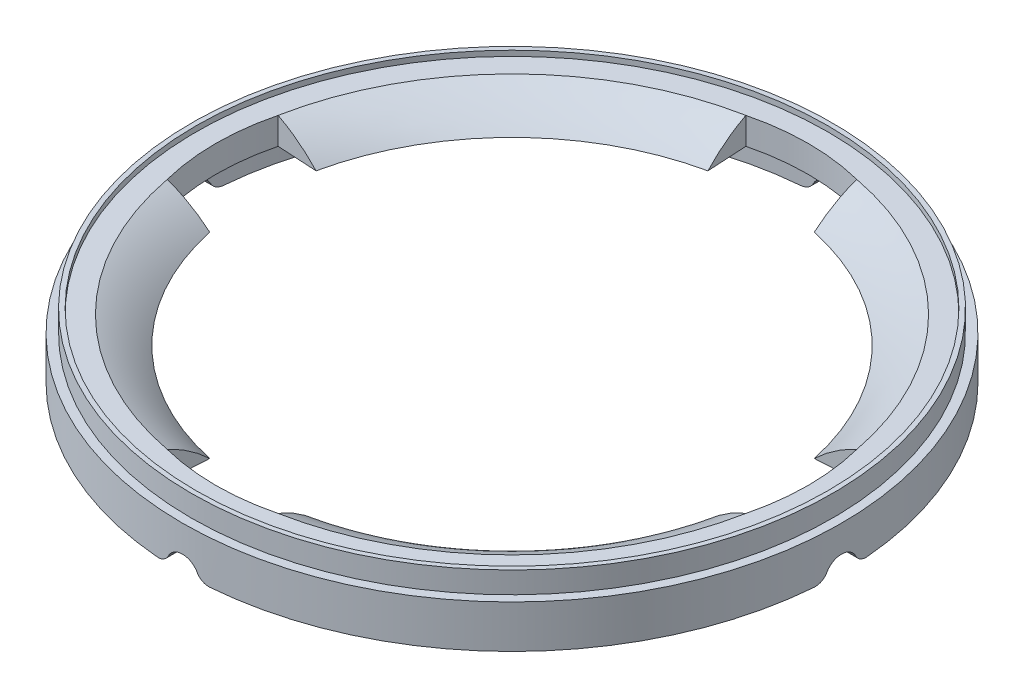
SolidWorks part; units mm, degrees
ref_plane "Front Plane" through (0, 0, 0) normal (0, 0, 1) x (1, 0, 0)
ref_plane "Top Plane" through (0, 0, 0) normal (0, 1, 0) x (1, 0, 0)
ref_plane "Right Plane" through (0, 0, 0) normal (1, 0, 0) x (0, 0, -1)
sketch "Sketch3" plane through (0, 0, 0) normal (0, 1, 0) x (1, 0, 0)
  circle A0 centre (0, 0) radius 61.468
  circle A1 centre (0, 0) radius 58.9503
  dimension "D1" = 122.936
  dimension "D2" = 117.9005
extrude "Boss-Extrude1" add sketch "Sketch3" along normal blind 8 contours A0 | A1
sketch "Sketch7" plane through (0, 8, 0) normal (0, 1, 0) x (1, 0, 0)
  circle A0 centre (0, 0) radius 58.9503 construction
  circle A1 centre (0, 0) radius 58.9503
  circle A2 centre (0, 0) radius 59.8203
  dimension "D1" = 0.87
extrude "Boss-Extrude2" add sketch "Sketch7" along normal blind 4
sketch "Sketch9" plane through (0, 0, 0) normal (0, 0, 1) x (1, 0, 0)
  line L0 (0, 8) -> (0, 0) construction
  line L2 (0, 0) -> (3, 0)
  line L3 (0, 0) -> (-3, 0)
  line L4 (-61.468, 0) -> (61.468, 0) construction
  arc A0 (-3, 0) -> (3, 0) centre (0, 0) cw
  point P0 (0, 2.1417)
  dimension "D1" = 3
  dimension "D3" = 3
  dimension "D2" = 3
extrude "Cut-Extrude1" cut sketch "Sketch9" along normal through all contours A0 L2 L3
fillet "Fillet1" radius 2.54 2 edges at (3, 0, 60.1343) (-3, 0, 60.1343)
pattern_circular "CirPattern1" count 4 every 90 about axis through (0, 8, 0) along (0, 1, 0) of "Fillet1", "Cut-Extrude1"
sketch "Sketch10" plane through (0, 0, 0) normal (0, 0, 1) x (1, 0, 0)
  line L0 (0, 0) -> (0, 25.483) construction
  line L4 (-58.9503, 6) -> (-47.5103, 6)
  line L5 (-58.9503, 11) -> (-58.9503, 6)
  line L6 (-58.9503, 12) -> (-58.9503, 2.9999) construction
  line L9 (-58.9503, 11) -> (-54.9503, 11)
  arc A0 (-54.9503, 11) -> (-47.5103, 6) centre (-64.949, -11.9134) cw
  dimension "D3" = 25
  dimension "D1" = 5
  dimension "D2" = 4
revolve "Revolve2" add sketch "Sketch10" angle 360 about L0
sketch "Sketch13" plane through (0, 0, 0) normal (0, 1, 0) x (1, 0, 0)
  line L0 (0, 0) -> (0, 71.5871) construction
  line L1 (-7.4918, 3.6826) -> (-10.3399, 53.9687)
  line L6 (7.5061, 3.9338) -> (10.3399, 53.9687)
  line L7 (-10.3399, 53.9687) -> (-7.4918, 3.6826)
  line L8 (10.3399, 53.9687) -> (7.5061, 3.9338)
  circle A0 centre (0, 0) radius 47.5103 construction
  arc A1 (-7.4918, 3.6826) -> (7.5061, 3.9338) centre (-0.3261, 23.7084) cw
  circle A2 centre (0, 0) radius 54.9503 construction
  arc A3 (-10.3399, 53.9687) -> (10.3399, 53.9687) centre (0, 13.1034) cw
  point P5 (0, 47.5103)
  point P13 (-4.4228, 53.8696)
  point P14 (0, 54.9503)
  point P15 (-5.1744, 54.9503)
  point P20 (5.1744, 54.9503)
  point P21 (4.4228, 53.8696)
  dimension "D1" = 15
extrude "Cut-Extrude4" cut sketch "Sketch13" along normal through all contours A1 L0 A3 L7 | L0 A1 L8 A3
pattern_circular "CirPattern3" count 4 every 90 about axis through (0, 0, 0) along (0, 1, 0) of "Cut-Extrude4"
